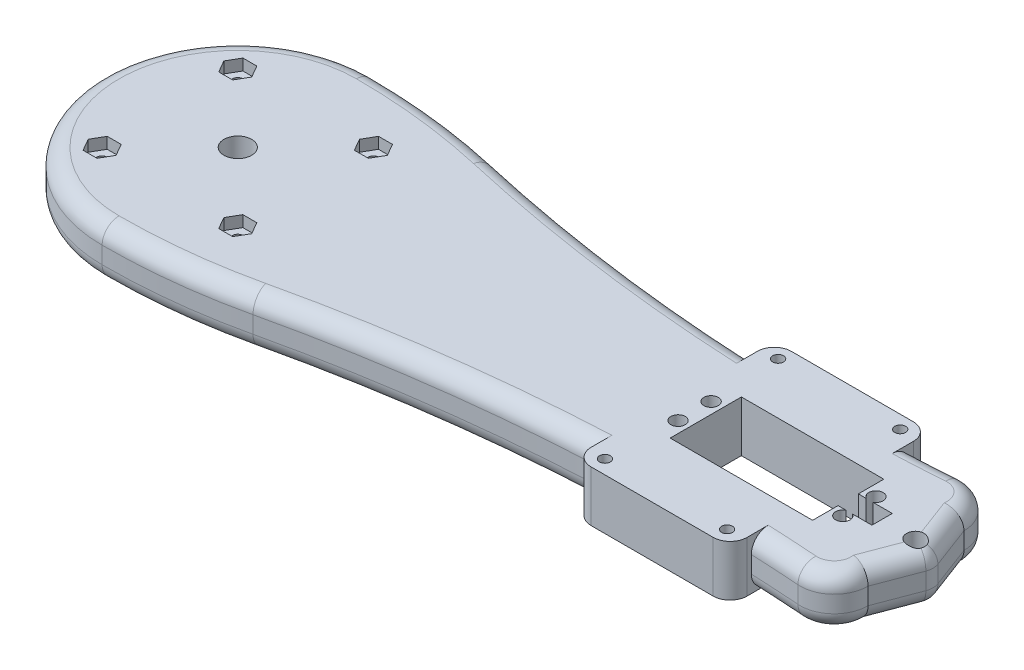
SolidWorks part; units mm, degrees
ref_plane "Alzado" through (0, 0, 0) normal (0, 0, 1) x (1, 0, 0)
ref_plane "Planta" through (0, 0, 0) normal (0, 1, 0) x (1, 0, 0)
ref_plane "Vista lateral" through (0, 0, 0) normal (1, 0, 0) x (0, 0, -1)
other "Centro de masa"
sketch "Croquis1" plane through (0, 0, 0) normal (0, 1, 0) x (1, 0, 0)
  line L0 (0, -40) -> (0, 40) construction
  line L1 (0, 0) -> (200, 0) construction
  line L2 (200, -25) -> (200, 25) construction
  line L3 (0, 35.5) -> (-18.4323, 35.5) construction
  line L4 (200, -25) -> (200, 25)
  arc A0 (0, 40) -> (0, -40) centre (0, 0) ccw
  arc A2 (0, 40) -> (40, 35.5) centre (0, -140.0278) cw
  arc A3 (40, 35.5) -> (200, 25) centre (152.8395, 530.6618) ccw
  arc A4 (40, -35.5) -> (200, -25) centre (152.8395, -530.6618) cw
  arc A5 (0, -40) -> (40, -35.5) centre (0, 140.0278) ccw
  dimension "D1" = 80
  dimension "D3" = 50
  dimension "D2" = 200
  dimension "D4" = 4.5
  dimension "D5" = 40
extrude "Saliente-Extruir1" add sketch "Croquis1" along normal blind 15
fillet "Redondeo5" [suppressed] radius 10
fillet "Redondeo2" radius 10 2 edges at (200, 7.5, 25) (200, 7.5, -25)
sketch "Croquis2" plane through (0, 0, 0) normal (0, -1, 0) x (1, 0, 0)
  line L0 (0, 0) -> (200, 0) construction
  line L1 (-20, 20) -> (20, 20) construction
  line L2 (-20, 20) -> (-20, -20) construction
  line L3 (-20, -20) -> (20, -20) construction
  line L4 (20, 20) -> (20, -20) construction
  line L5 (-20, 20) -> (20, -20) construction
  line L6 (-20, -20) -> (20, 20) construction
  line L7 (138, 10.5) -> (180, 10.5)
  line L8 (138, 10.5) -> (138, -10.5)
  line L9 (138, -10.5) -> (180, -10.5)
  line L10 (180, 10.5) -> (180, 3)
  line L11 (138, 10.5) -> (180, -10.5) construction
  line L12 (138, -10.5) -> (180, 10.5) construction
  line L13 (180, -3) -> (180, -10.5)
  line L14 (180, 3) -> (190, 3)
  line L16 (180, -3) -> (190, -3)
  line L17 (190, 3) -> (190, -3)
  line L18 (180, 3) -> (190, -3) construction
  line L19 (180, -3) -> (190, 3) construction
  circle A0 centre (-20, 20) radius 1.6
  circle A1 centre (20, 20) radius 1.6
  circle A2 centre (0, 0) radius 4.09
  circle A3 centre (20, -20) radius 1.6
  circle A4 centre (-20, -20) radius 1.6
  point P0 (0, 0)
  point P12 (159, 0)
  point P21 (185, 0)
  dimension "D2" = 3.2
  dimension "D3" = 8.18
  dimension "D1" = 40
  dimension "D4" = 21
  dimension "D5" = 42
  dimension "D6" = 20
  dimension "D7" = 6
  dimension "D8" = 10
extrude "Cortar-Extruir1" cut sketch "Croquis2" against normal through all
sketch "Croquis3" plane through (0, 0, 0) normal (0, -1, 0) x (1, 0, 0)
  line L0 (200, 14.1406) -> (204.677, 1.768)
  line L1 (200, 14.1406) -> (200, 5)
  line L2 (200, 14.1406) -> (200, -14.1406) construction
  line L3 (200, -14.1406) -> (200, -5)
  line L4 (200, -14.1406) -> (204.677, -1.768)
  line L5 (200, 14.1406) -> (200, -14.1406) construction
  arc A0 (204.677, 1.768) -> (204.677, -1.768) centre (200, 0) cw
  arc A1 (200, 5) -> (200, -5) centre (200, 0) ccw
  arc A2 (200, 5) -> (200, -5) centre (200, 0) cw construction
  point P9 (205, 0)
  point P11 (200, 0)
  point P13 (195, 0)
  dimension "D2" = 5
  dimension "D3" = 5
  dimension "D1" = 10
extrude "Saliente-Extruir2" add sketch "Croquis3" against normal through all
fillet "Redondeo8" [suppressed] radius 5
fillet "Redondeo9" [suppressed] radius 5
sketch "Croquis4" plane through (0, 15, 0) normal (0, 1, 0) x (1, 0, 0)
  circle A0 centre (199.87, 0) radius 2.075
extrude "Cortar-Extruir2" [suppressed] cut sketch "Croquis4" against normal through all
sketch "Croquis6" plane through (0, 15, 0) normal (0, 1, 0) x (1, 0, 0)
  line L0 (174.7, 23.2763) -> (174.7, 29.5163)
  line L1 (180, 10.5) -> (180, 3) construction
  line L2 (174.7, 29.5163) -> (128.7, 29.5163)
  line L3 (128.7, 29.5163) -> (128.7, 23.3796)
  line L4 (0, 0) -> (190, 0) construction
  line L5 (190, 3) -> (190, -3) construction
  line L6 (128.7, -29.5163) -> (128.7, -23.3796)
  line L7 (174.7, -23.2763) -> (174.7, -29.5163)
  line L8 (174.7, -29.5163) -> (128.7, -29.5163)
  arc A1 (40, 35.5) -> (189.2824, 24.1148) centre (152.8395, 530.6618) ccw construction
  arc A2 (128.7, 23.3796) -> (174.7, 23.2763) centre (152.8395, 530.6618) ccw
  arc A3 (128.7, -23.3796) -> (174.7, -23.2763) centre (152.8395, -530.6618) cw
  dimension "D1" = 5.3
  dimension "D2" = 6.24
  dimension "D3" = 46
extrude "Saliente-Extruir3" add sketch "Croquis6" against normal up to surface (15 mm away) up to face at (172, 0, 0)
fillet "Redondeo10" radius 5 24 edges at (181.9942, 15, 23.6431) (181.9942, 0, 23.6431) (196.8126, 15, -21.4609) (196.8126, 0, -21.4609) (84.0824, 15, -27.4815) (84.0824, 0, -27.4815) (20.1262, 0, -38.8715) (20.1262, 15, -38.8715) (84.0824, 15, 27.4815) (84.0824, 0, 27.4815) (20.1262, 0, 38.8715) (20.1262, 15, 38.8715) (196.8126, 15, 21.4609) (196.8126, 0, 21.4609) (202.3385, 0, 7.9543) (202.3385, 15, 7.9543) (202.3385, 0, -7.9543) (202.3385, 15, -7.9543) (181.9942, 15, -23.6431) (181.9942, 0, -23.6431) (-40, 0, 0) (-40, 15, 0) (205, 0, 0) (205, 15, 0)
fillet "Redondeo11" radius 5 4 edges at (128.7, 7.5, 29.5163) (174.7, 7.5, 29.5163) (174.7, 7.5, -29.5163) (128.7, 7.5, -29.5163)
sketch "Croquis11" plane through (0, 15, 0) normal (0, 1, 0) x (1, 0, 0)
  circle A0 centre (133.69, 25.265) radius 1.4218
sketch "Croquis12" plane through (0, 0, 0) normal (0, -1, 0) x (1, 0, 0)
  line L0 (169.7, 29.5163) -> (133.7, 29.5163) construction
  line L1 (128.7, 24.5163) -> (128.7, 18.374) construction
  line L2 (174.7, 18.2717) -> (174.7, 24.5163) construction
  line L3 (133.7, -29.5163) -> (169.7, -29.5163) construction
  line L4 (128.7, -18.374) -> (128.7, -24.5163) construction
  line L5 (174.7, -24.5163) -> (174.7, -18.2717) construction
  circle A0 centre (133.69, 25.4163) radius 1.6
  circle A1 centre (169.69, 25.4163) radius 1.6
  circle A2 centre (133.69, -25.6363) radius 1.6
  circle A3 centre (169.69, -25.6363) radius 1.6
  dimension "D1" = 3.2
  dimension "D2" = 4.1
  dimension "D3" = 4.99
  dimension "D4" = 4.1
  dimension "D5" = 5.01
  dimension "D6" = 3.88
  dimension "D7" = 4.99
  dimension "D8" = 3.88
  dimension "D9" = 5.01
extrude "Cortar-Extruir3" cut sketch "Croquis12" against normal up to next
sketch "Croquis13" plane through (0, 0, 0) normal (0, -1, 0) x (1, 0, 0)
  line L0 (180, 3) -> (180, 10.5) construction
  line L1 (138, -10.5) -> (180, -10.5) construction
  circle A0 centre (199.87, 0) radius 2.675
  dimension "D1" = 5.35
  dimension "D2" = 19.87
  dimension "D3" = 10.5
extrude "Cortar-Extruir4" cut sketch "Croquis13" against normal up to next
sketch "Croquis14" plane through (0, 15, 0) normal (0, 1, 0) x (1, 0, 0)
  circle A0 centre (183.3, 4.875) radius 2.125
  circle A1 centre (183.3, -4.875) radius 2.125
  circle A2 centre (134.7, 4.875) radius 2.125
  circle A3 centre (134.7, -4.875) radius 2.125
  point P8 (134.7, -4.875)
  point P9 (134.7, 4.875)
  dimension "D1" = 4.25
extrude "Cortar-Extruir5" cut sketch "Croquis14" against normal through all
sketch "Croquis15" plane through (0, 15, 0) normal (0, 1, 0) x (1, 0, 0)
  line L1 (-15.8893, 20) -> (-17.9446, 23.56)
  line L2 (-17.9446, 23.56) -> (-22.0554, 23.56)
  line L3 (-22.0554, 23.56) -> (-24.1107, 20)
  line L4 (-24.1107, 20) -> (-22.0554, 16.44)
  line L5 (-22.0554, 16.44) -> (-17.9446, 16.44)
  line L6 (-17.9446, 16.44) -> (-15.8893, 20)
  line L7 (22.0554, 23.56) -> (17.9446, 23.56)
  line L8 (17.9446, 23.56) -> (15.8893, 20)
  line L9 (15.8893, 20) -> (17.9446, 16.44)
  line L10 (17.9446, 16.44) -> (22.0554, 16.44)
  line L11 (22.0554, 16.44) -> (24.1107, 20)
  line L12 (24.1107, 20) -> (22.0554, 23.56)
  line L13 (24.1107, -20) -> (22.0554, -16.44)
  line L14 (22.0554, -16.44) -> (17.9446, -16.44)
  line L15 (17.9446, -16.44) -> (15.8893, -20)
  line L16 (15.8893, -20) -> (17.9446, -23.56)
  line L17 (17.9446, -23.56) -> (22.0554, -23.56)
  line L18 (22.0554, -23.56) -> (24.1107, -20)
  line L19 (-15.8893, -20) -> (-17.9446, -16.44)
  line L20 (-17.9446, -16.44) -> (-22.0554, -16.44)
  line L21 (-22.0554, -16.44) -> (-24.1107, -20)
  line L22 (-24.1107, -20) -> (-22.0554, -23.56)
  line L23 (-22.0554, -23.56) -> (-17.9446, -23.56)
  line L24 (-17.9446, -23.56) -> (-15.8893, -20)
  circle A0 centre (-20, 20) radius 3.56 construction
  circle A1 centre (20, 20) radius 3.56 construction
  circle A2 centre (20, -20) radius 3.56 construction
  circle A3 centre (-20, -20) radius 3.56 construction
  dimension "D1" = 7.12
extrude "Cortar-Extruir6" cut sketch "Croquis15" against normal blind 3.32
